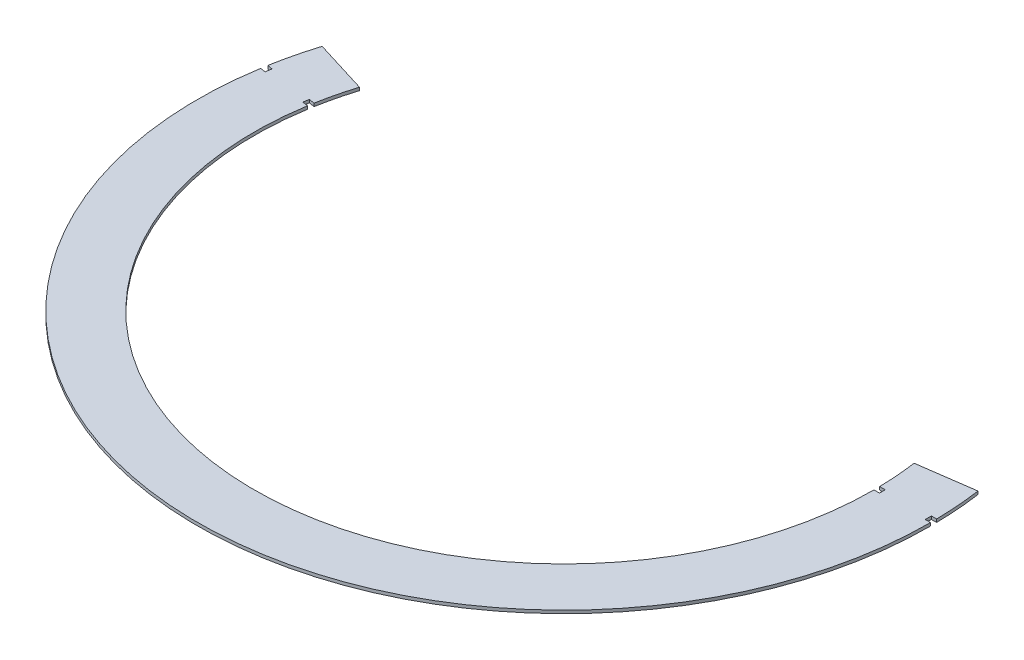
SolidWorks part; units mm, degrees
ref_plane "Front Plane" through (0, 0, 0) normal (0, 0, 1) x (1, 0, 0)
ref_plane "Top Plane" through (0, 0, 0) normal (0, 1, 0) x (1, 0, 0)
ref_plane "Right Plane" through (0, 0, 0) normal (1, 0, 0) x (0, 0, -1)
sketch "Sketch3" plane through (0, 0, 0) normal (0, 1, 0) x (1, 0, 0)
  line L0 (-70.3098, 11.3499) -> (-83.1437, 13.4217)
  line L1 (71.22, 0) -> (84.22, 0)
  arc A0 (-83.1437, 13.4217) -> (84.22, 0) centre (0, 0) ccw
  arc A1 (71.22, 0) -> (-70.3098, 11.3499) centre (0, 0) cw
  dimension "D1" = 13
  dimension "D2" = 84.22
  dimension "D3" = 170.83
extrude "Boss-Extrude1" add sketch "Sketch3" along normal blind 0.7
sketch "Sketch4" plane through (0, 0, 0) normal (0, 1, 0) x (1, 0, 0)
  line L0 (70.5269, 9.9119) -> (83.4004, 11.7212)
  line L1 (71.2082, 1.2973) -> (84.2082, 1.4107)
  line L2 (-0.385, 0) -> (0.385, 0) construction
  line L3 (72.5, 1.3086) -> (72.5, 0)
  line L4 (83, 1.4002) -> (83, 0)
  line L5 (71.22, 0) -> (84.22, 0)
  arc A0 (71.22, 0) -> (70.5269, 9.9119) centre (0, 0) ccw
  arc A1 (84.22, 0) -> (83.4004, 11.7212) centre (0, 0) ccw
  arc A2 (-83.1437, 13.4217) -> (84.22, 0) centre (0, 0) ccw construction
  arc A3 (-70.3098, 11.3499) -> (71.22, 0) centre (0, 0) ccw construction
  arc A4 (-83.1437, 13.4217) -> (84.22, 0) centre (0, 0) ccw construction
  arc A5 (-70.3098, 11.3499) -> (71.22, 0) centre (0, 0) ccw construction
  point P21 (71.1727, 0)
  dimension "D5" = 72.5
  dimension "D6" = 83
  dimension "D1" = 8
  dimension "D2" = 13
  dimension "D3" = 0.5
  dimension "D4" = 13
extrude "notch" add sketch "Sketch4" along normal up to surface (0.7 mm away) contours L3 L5 L4 L1 | L1 A1 L0 A0 up to face at (-2.8581, 0.7, 35.6392)
ref_plane "Plane1" through (0, 0, 0) normal (-0.9968, 0, -0.0799) x (-0.0799, 0, 0.9968)
mirror "Mirror1" about plane through (0, 0, 0) normal (-0.9968, 0, -0.0799) of "notch"
